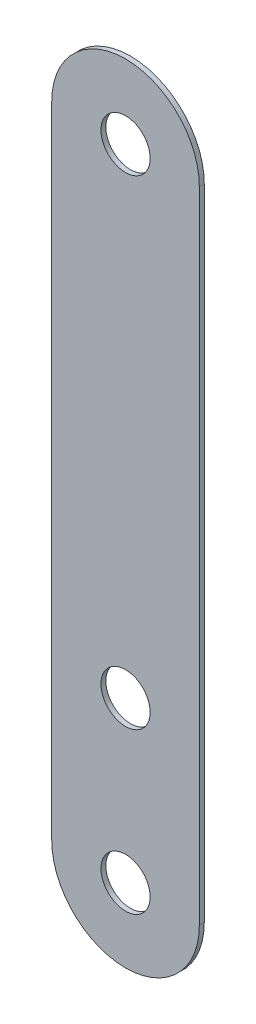
SolidWorks part; units mm, degrees
ref_plane "Спереди" through (0, 0, 0) normal (0, 0, 1) x (1, 0, 0)
ref_plane "Сверху" through (0, 0, 0) normal (0, 1, 0) x (1, 0, 0)
ref_plane "Справа" through (0, 0, 0) normal (1, 0, 0) x (0, 0, -1)
sketch "Эскиз1" plane through (0, 0, 0) normal (0, 0, 1) x (1, 0, 0)
  line L2 (0, 0) -> (0, 130)
  line L4 (30, 0) -> (30, 130)
  arc A0 (30, 130) -> (0, 130) centre (15, 130) ccw
  arc A1 (0, 0) -> (30, 0) centre (15, 0) ccw
  circle A2 centre (15, 130) radius 5
  circle A3 centre (15, 0) radius 5
  circle A4 centre (15, 32.5) radius 5
  dimension "D6" = 10
  dimension "D7" = 10
  dimension "D9" = 10
  dimension "D1" = 130
  dimension "D2" = 30
  dimension "D3" = 15
  dimension "D4" = 15
  dimension "D5" = 130
  dimension "D8" = 32.5
extrude "Бобышка-Вытянуть1" add sketch "Эскиз1" along normal blind 1
